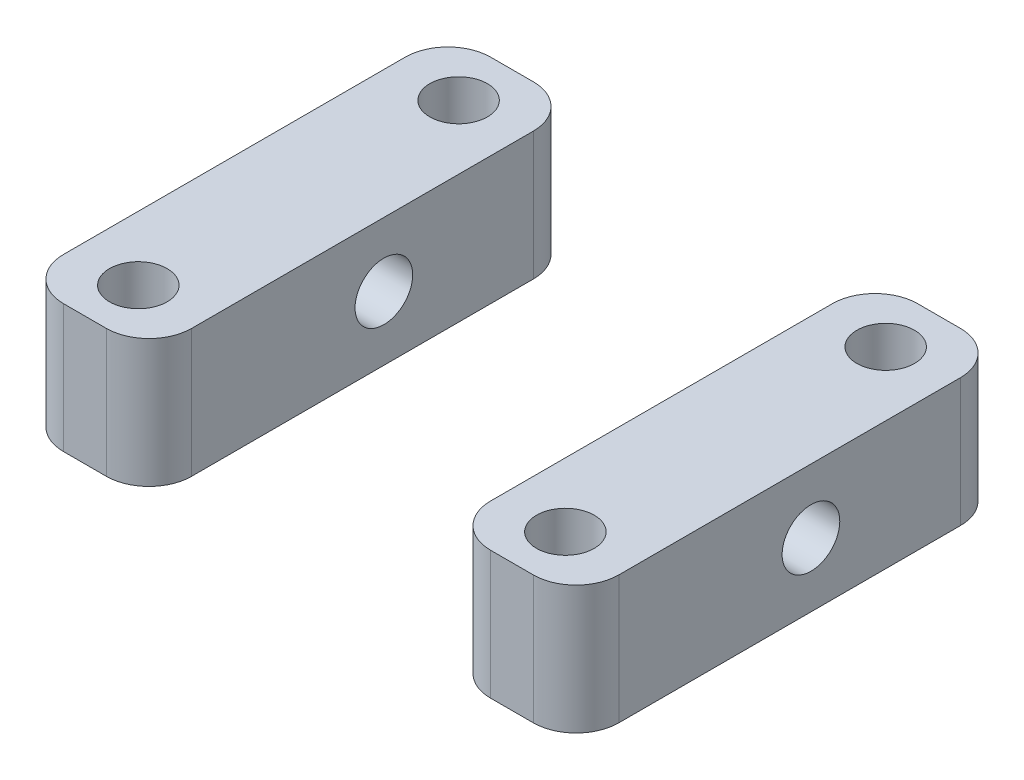
SolidWorks part; units mm, degrees
material "PLA"
ref_plane "前视基准面" through (0, 0, 0) normal (0, 0, 1) x (1, 0, 0)
ref_plane "上视基准面" through (0, 0, 0) normal (0, 1, 0) x (1, 0, 0)
ref_plane "右视基准面" through (0, 0, 0) normal (1, 0, 0) x (0, 0, -1)
sketch "草图1" plane through (0, 0, 0) normal (0, 1, 0) x (1, 0, 0)
  line L1 (-13, -10) -> (13, -10)
  line L2 (-13, -10) -> (-13, 10)
  line L3 (-13, 10) -> (13, 10)
  line L4 (13, -10) -> (13, 10)
  line L5 (0, 10) -> (0, -10) construction
  line L6 (-13, 0) -> (13, 0) construction
  circle A0 centre (-10, 7.5) radius 1.35
  circle A1 centre (10, 7.5) radius 1.35
  circle A2 centre (10, -7.5) radius 1.35
  circle A3 centre (-10, -7.5) radius 1.35
  point P0 (0, 0)
  dimension "D5" = 2.7
  dimension "D1" = 15
  dimension "D2" = 3
  dimension "D3" = 26
  dimension "D4" = 20
extrude "凸台-拉伸1" add sketch "草图1" along normal blind 6
sketch "草图2" plane through (0, 6, 0) normal (0, 1, 0) x (1, 0, 0)
  line L0 (-13, -10) -> (13, -10) construction
  line L1 (7, 10) -> (-7, 10)
  line L2 (7, 10) -> (7, -10)
  line L3 (7, -10) -> (-7, -10)
  line L4 (-7, 10) -> (-7, -10)
  line L5 (0, -10) -> (0, 10) construction
  line L6 (7, 0) -> (-7, 0) construction
  line L7 (-13, 10) -> (-13, -10) construction
  point P0 (0, 0)
  dimension "D1" = 6
extrude "切除-拉伸1" cut sketch "草图2" against normal through all
sketch "草图5" plane through (13, 0, 0) normal (1, 0, 0) x (0, 0, -1)
  line L0 (10, 3) -> (-10, 3) construction
  line L1 (10, 6) -> (10, 0) construction
  line L2 (-10, 6) -> (-10, 0) construction
  circle A0 centre (1, 3) radius 1.35
  dimension "D2" = 2.7
  dimension "D1" = 9
extrude "切除-拉伸2" cut sketch "草图5" against normal through all
fillet "圆角1" radius 2 4 edges at (13, 3, 10) (13, 3, -10) (7, 3, -10) (7, 3, 10)
fillet "圆角2" radius 2 4 edges at (-13, 3, -10) (-7, 3, -10) (-7, 3, 10) (-13, 3, 10)
move or copy body "实体-移动/复制1" [suppressed] bodies to move or copy 109 110
